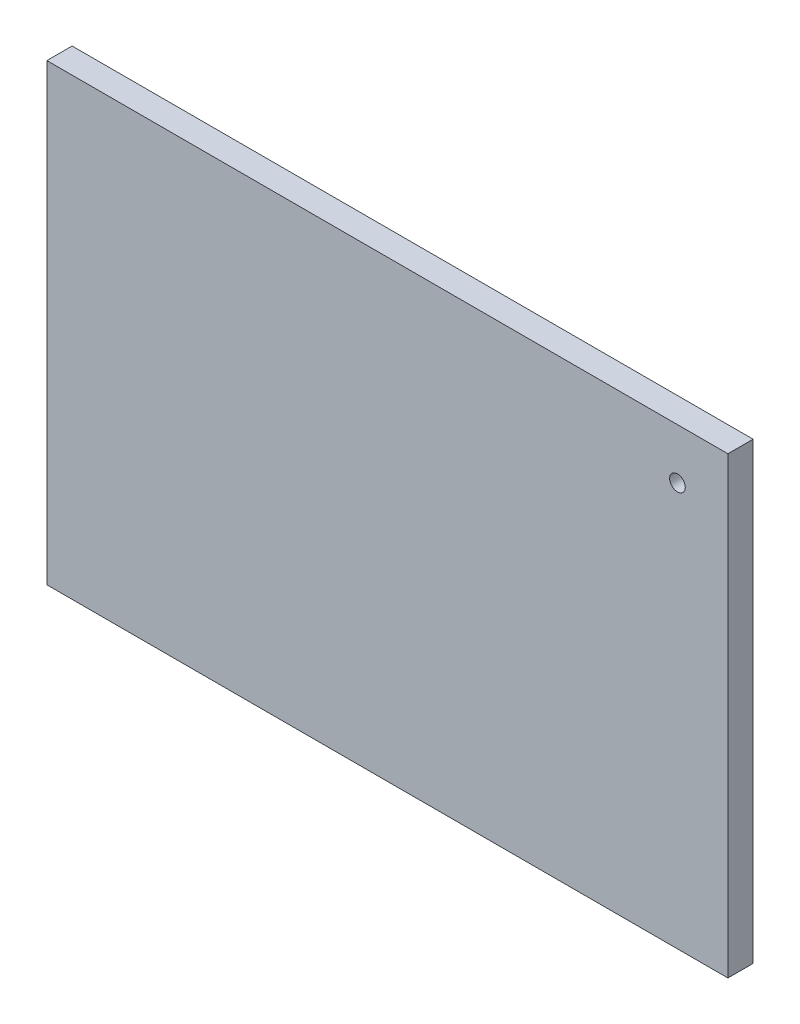
SolidWorks part; units mm, degrees
ref_plane "Plan de face" through (0, 0, 0) normal (0, 0, 1) x (1, 0, 0)
ref_plane "Plan de dessus" through (0, 0, 0) normal (0, 1, 0) x (1, 0, 0)
ref_plane "Plan de droite" through (0, 0, 0) normal (1, 0, 0) x (0, 0, -1)
sketch "Esquisse1" plane through (0, 0, 0) normal (0, 0, 1) x (1, 0, 0)
  line L1 (-67.5, -45) -> (67.5, -45)
  line L2 (-67.5, -45) -> (-67.5, 45)
  line L3 (-67.5, 45) -> (67.5, 45)
  line L4 (67.5, -45) -> (67.5, 45)
  line L5 (-67.5, -45) -> (67.5, 45) construction
  line L6 (-67.5, 45) -> (67.5, -45) construction
  circle A0 centre (57.5, 35) radius 1.55
  point P0 (0, 0)
  dimension "D3" = 3.1
  dimension "D1" = 135
  dimension "D2" = 90
  dimension "D4" = 10
  dimension "D5" = 10
extrude "Boss.-Extru.1" add sketch "Esquisse1" along normal blind 5
